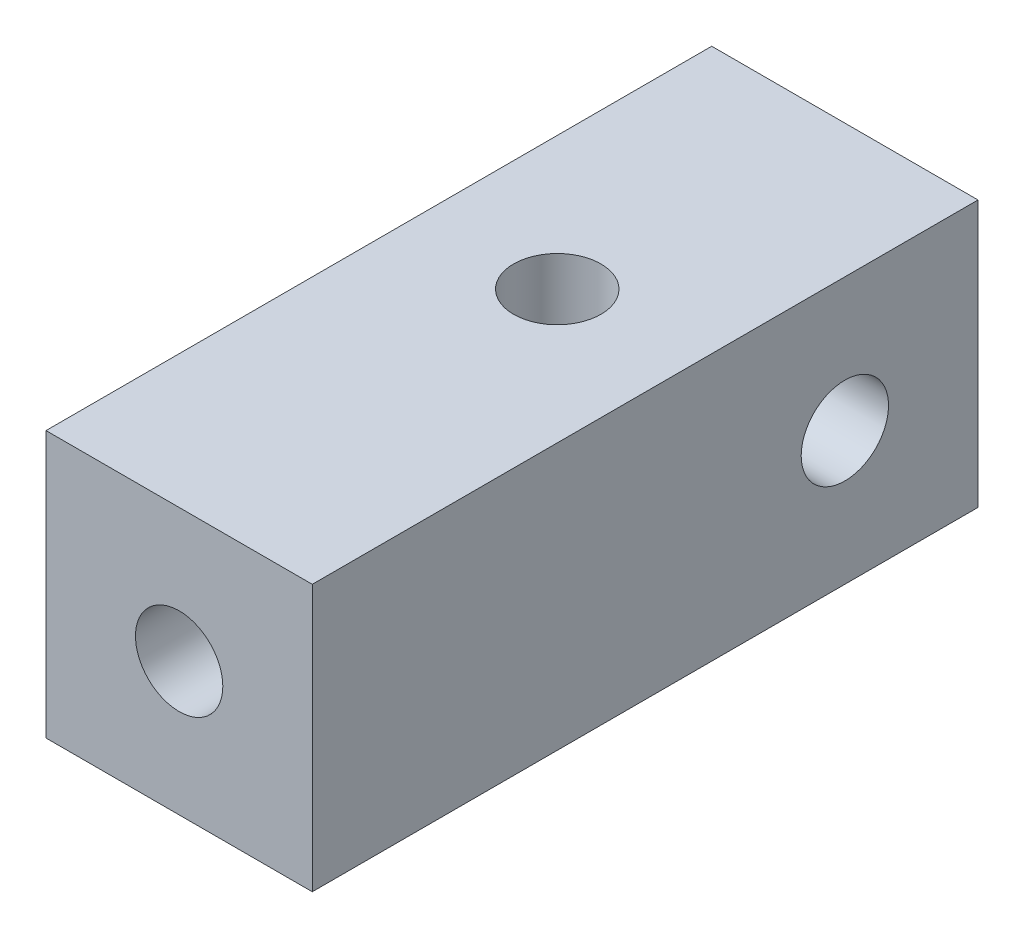
SolidWorks part; units mm, degrees
ref_plane "Front Plane" through (0, 0, 0) normal (0, 0, 1) x (1, 0, 0)
ref_plane "Top Plane" through (0, 0, 0) normal (0, 1, 0) x (1, 0, 0)
ref_plane "Right Plane" through (0, 0, 0) normal (1, 0, 0) x (0, 0, -1)
sketch "Sketch1" plane through (0, 0, 0) normal (0, 1, 0) x (1, 0, 0)
  line L0 (0, 0) -> (0, 31.75)
  line L1 (0, 31.75) -> (12.7, 31.75)
  line L2 (12.7, 31.75) -> (12.7, 0)
  line L3 (12.7, 0) -> (0, 0)
  line L4 (6.35, 0) -> (6.35, 18.034) construction
  circle A0 centre (6.35, 18.034) radius 2.0828
  dimension "D1" = 18.034
extrude "Boss-Extrude1" add sketch "Sketch1" along normal blind 12.7
sketch "Sketch2" plane through (0, 0, 0) normal (0, 0, 1) x (1, 0, 0)
  line L0 (6.35, 0) -> (6.35, 6.35) construction
  line L1 (0, 0) -> (12.7, 0) construction
  circle A0 centre (6.35, 6.35) radius 2.0828
extrude "Cut-Extrude1" cut sketch "Sketch2" against normal blind 12.7
sketch "Sketch3" plane through (0, 0, 0) normal (-1, 0, 0) x (0, 0, 1)
  line L0 (-31.75, 6.35) -> (-25.4, 6.35) construction
  line L1 (-31.75, 12.7) -> (-31.75, 0) construction
  line L2 (0, 12.7) -> (0, 0) construction
  circle A0 centre (-25.4, 6.35) radius 2.0828
  dimension "D1" = 25.4
extrude "Cut-Extrude2" cut sketch "Sketch3" against normal blind 12.7
